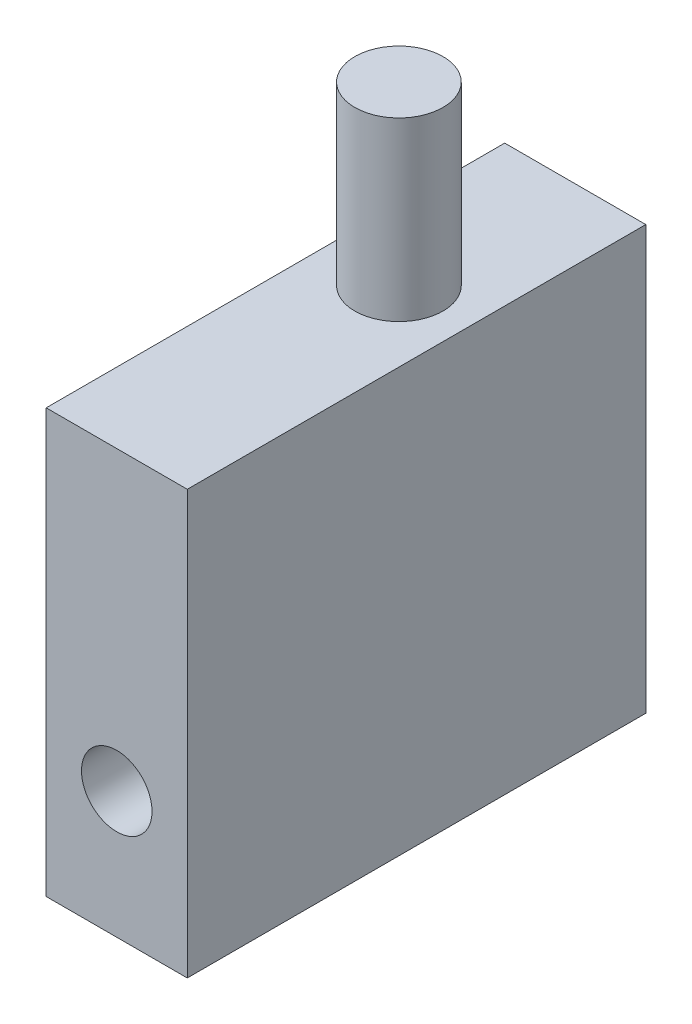
SolidWorks part; units mm, degrees
ref_plane "前视基准面" through (0, 0, 0) normal (0, 0, 1) x (1, 0, 0)
ref_plane "上视基准面" through (0, 0, 0) normal (0, 1, 0) x (1, 0, 0)
ref_plane "右视基准面" through (0, 0, 0) normal (1, 0, 0) x (0, 0, -1)
sketch "草图1" plane through (0, 0, 0) normal (0, 0, 1) x (1, 0, 0)
  line L1 (0, 0) -> (4, 0)
  line L2 (0, 0) -> (0, 12)
  line L3 (0, 12) -> (4, 12)
  line L4 (4, 0) -> (4, 12)
extrude "凸台-拉伸1" add sketch "草图1" along normal blind 13
sketch "草图2" plane through (0, 12, 0) normal (0, 1, 0) x (1, 0, 0)
  circle A0 centre (2, -5) radius 1.25
extrude "凸台-拉伸2" add sketch "草图2" along normal blind 5
sketch "草图3" plane through (0, 0, 13) normal (0, 0, 1) x (1, 0, 0)
  circle A0 centre (2, 3.59) radius 1
extrude "切除-拉伸1" cut sketch "草图3" against normal through all
